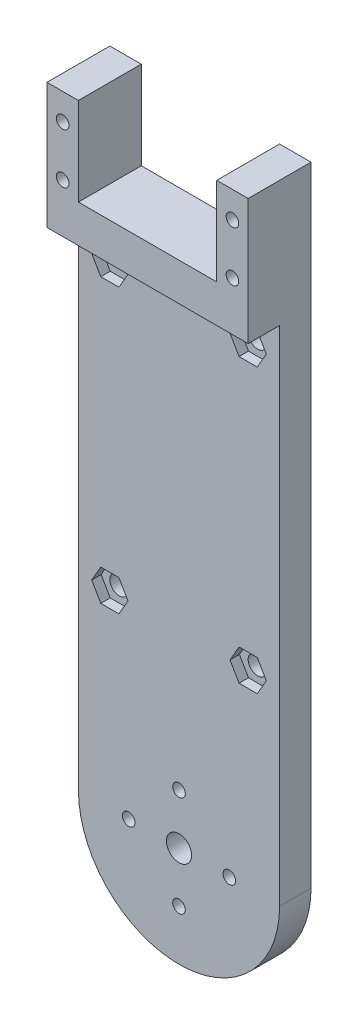
SolidWorks part; units mm, degrees
ref_plane "Front Plane" through (0, 0, 0) normal (0, 0, 1) x (1, 0, 0)
ref_plane "Top Plane" through (0, 0, 0) normal (0, 1, 0) x (1, 0, 0)
ref_plane "Right Plane" through (0, 0, 0) normal (1, 0, 0) x (0, 0, -1)
sketch "Sketch1" plane through (0, 0, 0) normal (0, 0, 1) x (1, 0, 0)
  line L0 (0, 0) -> (0, -8) construction
  line L1 (-16, 0) -> (-16, 80)
  line L2 (16, 0) -> (16, 80)
  line L3 (-16, 80) -> (16, 80)
  arc A0 (-16, 0) -> (16, 0) centre (0, 0) ccw
  circle A1 centre (0, 0) radius 2
  circle A2 centre (0, -8) radius 1
  circle A3 centre (0, 0) radius 2
  circle A4 centre (-8, 0) radius 1
  circle A5 centre (0, 0) radius 2
  circle A6 centre (0, 8) radius 1
  circle A7 centre (0, 0) radius 2
  circle A8 centre (8, 0) radius 1
  circle A9 centre (11, 75) radius 1.5
  circle A10 centre (-11, 75) radius 1.5
  circle A11 centre (-11, 30) radius 1.5
  circle A14 centre (11, 30) radius 1.5
  circle A17 centre (-11, -60) radius 1.5 [skipped]
  circle A18 centre (-11, -15) radius 1.5 [skipped]
  circle A19 centre (11, -60) radius 1.5 [skipped]
  circle A20 centre (11, -15) radius 1.5 [skipped]
  point P26 (0, 0)
  point P28 (0, 0)
  dimension "D1" = 32
  dimension "D2" = 4
  dimension "D3" = 2
  dimension "D7" = 3
  dimension "D4" = 8
  dimension "D6" = 80
  dimension "D8" = 5
  dimension "D9" = 5
  dimension "D10" = 5
  dimension "D12" = 45
  dimension "D14" = 45
  dimension "D11" = 4
  dimension "D13" = 4
  dimension "D5" = 4
extrude "Boss-Extrude1" add sketch "Sketch1" along normal blind 5
sketch "Sketch3" plane through (0, 0, 0) normal (0, 0, 1) x (1, 0, 0)
  line L0 (16, 0) -> (16, 80) construction
  line L1 (-16, 80) -> (16, 80)
  line L2 (-16, 80) -> (-16, 100)
  line L3 (-16, 100) -> (-11, 100)
  line L4 (16, 80) -> (16, 100)
  line L5 (11, 100) -> (16, 100)
  line L7 (-11, 100) -> (-11, 86)
  line L9 (11, 100) -> (11, 86)
  line L10 (-11, 86) -> (11, 86)
  line L11 (-16, 80) -> (16, 80) construction
  circle A0 centre (-13.5, 95.8) radius 1
  circle A1 centre (13.5, 95.8) radius 1
  circle A2 centre (13.5, 87.8) radius 1
  circle A3 centre (-13.5, 87.8) radius 1
  point P16 (15.7808, 80)
  point P23 (0, 0)
  point P24 (6.0115, 80)
  dimension "D2" = 2
  dimension "D6" = 7.8
  dimension "D1" = 20
  dimension "D3" = 2.5
  dimension "D4" = 2.5
  dimension "D5" = 8
  dimension "D7" = 5
  dimension "D8" = 5
  dimension "D10" = 6
extrude "Boss-Extrude2" add sketch "Sketch3" along normal blind 10
sketch "Sketch5" plane through (0, 0, 5) normal (0, 0, 1) x (1, 0, 0)
  line L1 (-8.1132, 75) -> (-9.5566, 77.5)
  line L2 (-9.5566, 77.5) -> (-12.4434, 77.5)
  line L3 (-12.4434, 77.5) -> (-13.8868, 75)
  line L4 (-13.8868, 75) -> (-12.4434, 72.5)
  line L5 (-12.4434, 72.5) -> (-9.5566, 72.5)
  line L6 (-9.5566, 72.5) -> (-8.1132, 75)
  line L7 (-8.1132, 30) -> (-9.5566, 32.5)
  line L8 (-9.5566, 32.5) -> (-12.4434, 32.5)
  line L9 (-12.4434, 32.5) -> (-13.8868, 30)
  line L10 (-13.8868, 30) -> (-12.4434, 27.5)
  line L11 (-12.4434, 27.5) -> (-9.5566, 27.5)
  line L12 (-9.5566, 27.5) -> (-8.1132, 30)
  line L13 (13.8868, 30) -> (12.4434, 32.5)
  line L14 (12.4434, 32.5) -> (9.5566, 32.5)
  line L15 (9.5566, 32.5) -> (8.1132, 30)
  line L16 (8.1132, 30) -> (9.5566, 27.5)
  line L17 (9.5566, 27.5) -> (12.4434, 27.5)
  line L18 (12.4434, 27.5) -> (13.8868, 30)
  line L19 (13.8868, 75) -> (12.4434, 77.5)
  line L20 (12.4434, 77.5) -> (9.5566, 77.5)
  line L21 (9.5566, 77.5) -> (8.1132, 75)
  line L22 (8.1132, 75) -> (9.5566, 72.5)
  line L23 (9.5566, 72.5) -> (12.4434, 72.5)
  line L24 (12.4434, 72.5) -> (13.8868, 75)
  circle A0 centre (-11, 75) radius 2.5 construction
  circle A1 centre (-11, 30) radius 2.5 construction
  circle A2 centre (11, 30) radius 2.5 construction
  circle A3 centre (11, 75) radius 2.5 construction
  dimension "D1" = 5
extrude "Cut-Extrude1" cut sketch "Sketch5" against normal blind 1.5
